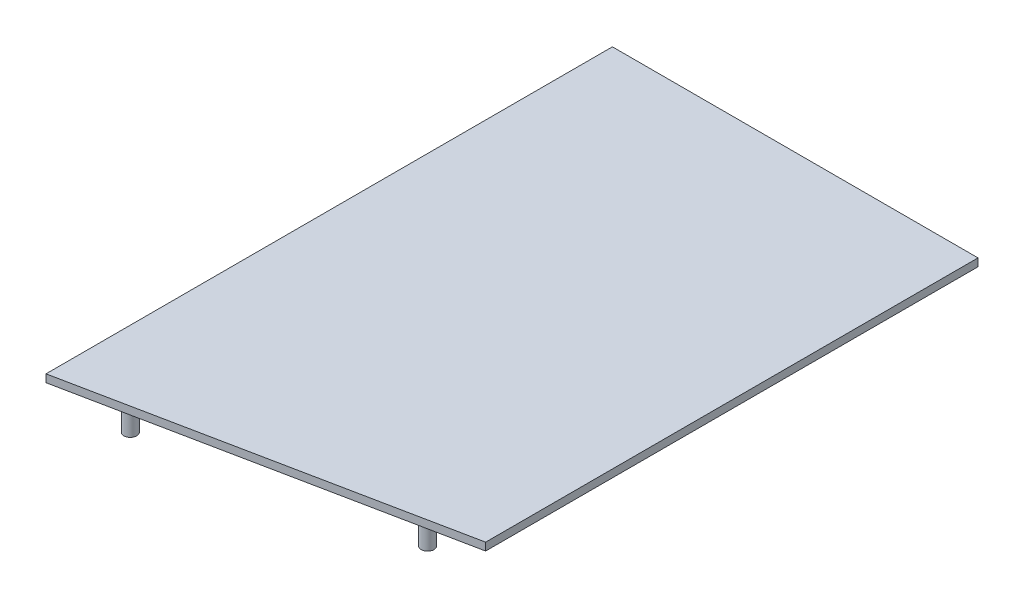
SolidWorks part; units mm, degrees
ref_plane "Front Plane" through (0, 0, 0) normal (0, 0, 1) x (1, 0, 0)
ref_plane "Top Plane" through (0, 0, 0) normal (0, 1, 0) x (1, 0, 0)
ref_plane "Right Plane" through (0, 0, 0) normal (1, 0, 0) x (0, 0, -1)
sketch "Sketch1" plane through (0, 0, 0) normal (0, 1, 0) x (1, 0, 0)
  line L0 (0, 0) -> (71, 14.38)
  line L2 (0, 0) -> (0, 110)
  line L3 (0, 110) -> (71, 110)
  line L4 (71, 14.38) -> (71, 110)
  dimension "D1" = 71
  dimension "D2" = 95.62
  dimension "D3" = 110
extrude "Boss-Extrude1" add sketch "Sketch1" along normal blind 1.5
sketch "Sketch2" plane through (0, 1.5, 0) normal (0, 1, 0) x (1, 0, 0)
  line L0 (0, 110) -> (0, 0) construction
  line L1 (10, 108.75) -> (12.5, 108.75)
  line L2 (10, 108.75) -> (10, 106.25)
  line L3 (10, 106.25) -> (12.5, 106.25)
  line L4 (12.5, 108.75) -> (12.5, 106.25)
  line L5 (71, 110) -> (0, 110) construction
  line L6 (0, 0) -> (71, 14.38) construction
  circle A0 centre (11.5, 4.8799) radius 1.25
  circle A1 centre (59.5, 14.6016) radius 1.25
  point P14 (0, 0)
  dimension "D5" = 11.5
  dimension "D6" = 2.5
  dimension "D7" = 2.5
  dimension "D8" = 48
  dimension "D9" = 2.5
  dimension "D10" = 2.5
  dimension "D1" = 2.5
  dimension "D2" = 2.5
  dimension "D3" = 10
  dimension "D4" = 1.25
extrude "Boss-Extrude2" add sketch "Sketch2" against normal blind 6.5
sketch "Sketch3" plane through (0, 0, 0) normal (0, -1, 0) x (-1, 0, 0)
  line L0 (-66, 105) -> (-66, 18.4688)
  line L1 (-66, 18.4688) -> (-5, 6.1142)
  line L2 (-5, 6.1142) -> (-5, 105)
  line L3 (-66, 105) -> (-5, 105)
  line L4 (-71, 14.38) -> (-71, 110) construction
  line L5 (-71, 110) -> (0, 110) construction
  line L6 (0, 110) -> (0, 0) construction
  line L7 (-71, 14.38) -> (-71, 110) construction
  line L8 (0, 0) -> (-71, 14.38) construction
  dimension "D1" = 5
  dimension "D2" = 5
  dimension "D3" = 5
  dimension "D4" = 5
  dimension "D5" = 5
  dimension "D6" = 5
  dimension "D7" = 5
  dimension "D8" = 5
extrude "Cut-Extrude1" cut sketch "Sketch3" against normal blind 0.6
